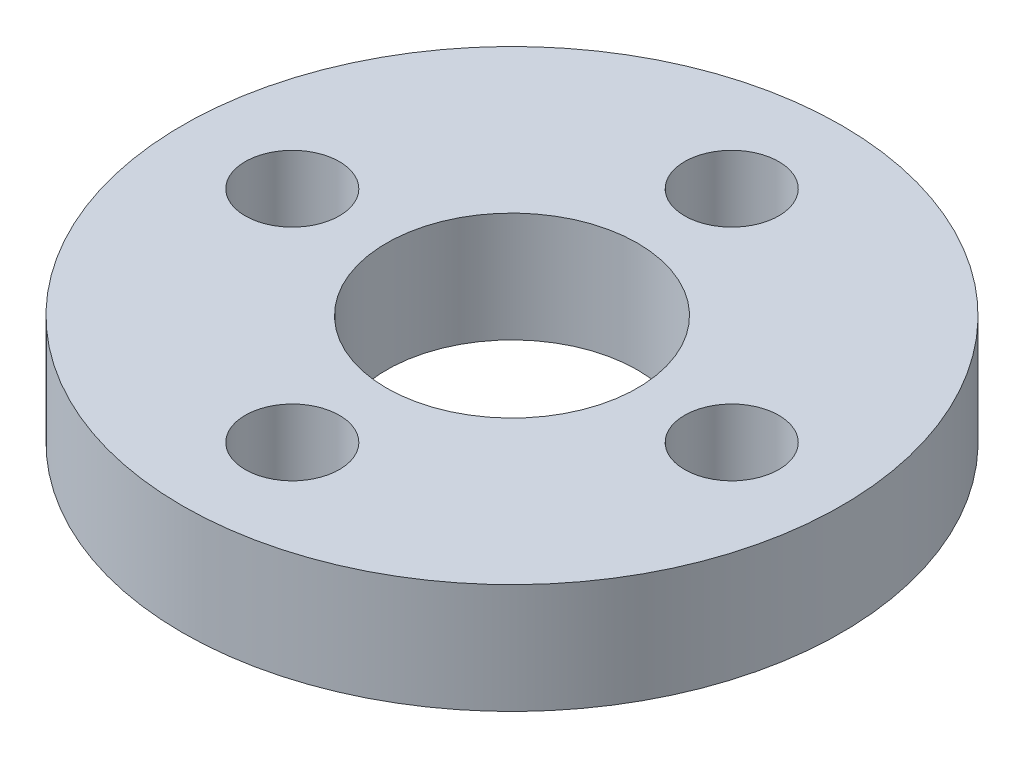
SolidWorks part; units mm, degrees
material "PE High Density"
ref_plane "Front Plane" through (0, 0, 0) normal (0, 0, 1) x (1, 0, 0)
ref_plane "Top Plane" through (0, 0, 0) normal (0, 1, 0) x (1, 0, 0)
ref_plane "Right Plane" through (0, 0, 0) normal (1, 0, 0) x (0, 0, -1)
sketch "Sketch1" plane through (0, 0, 0) normal (0, 1, 0) x (1, 0, 0)
  circle A0 centre (0, 0) radius 10.5
  dimension "D1" = 21
extrude "Boss-Extrude1" add sketch "Sketch1" along normal blind 3.5
sketch "Sketch2" plane through (0, 3.5, 0) normal (0, 1, 0) x (1, 0, 0)
  line L0 (0, 0) -> (0, 7) construction
  circle A0 centre (0, 0) radius 4
  circle A1 centre (0, 7) radius 1.5
  circle A2 centre (7, 0) radius 1.5
  circle A3 centre (0, -7) radius 1.5
  circle A4 centre (-7, 0) radius 1.5
  point P14 (0, 0)
  dimension "D1" = 4
extrude "Cut-Extrude1" cut sketch "Sketch2" against normal blind 10.2
